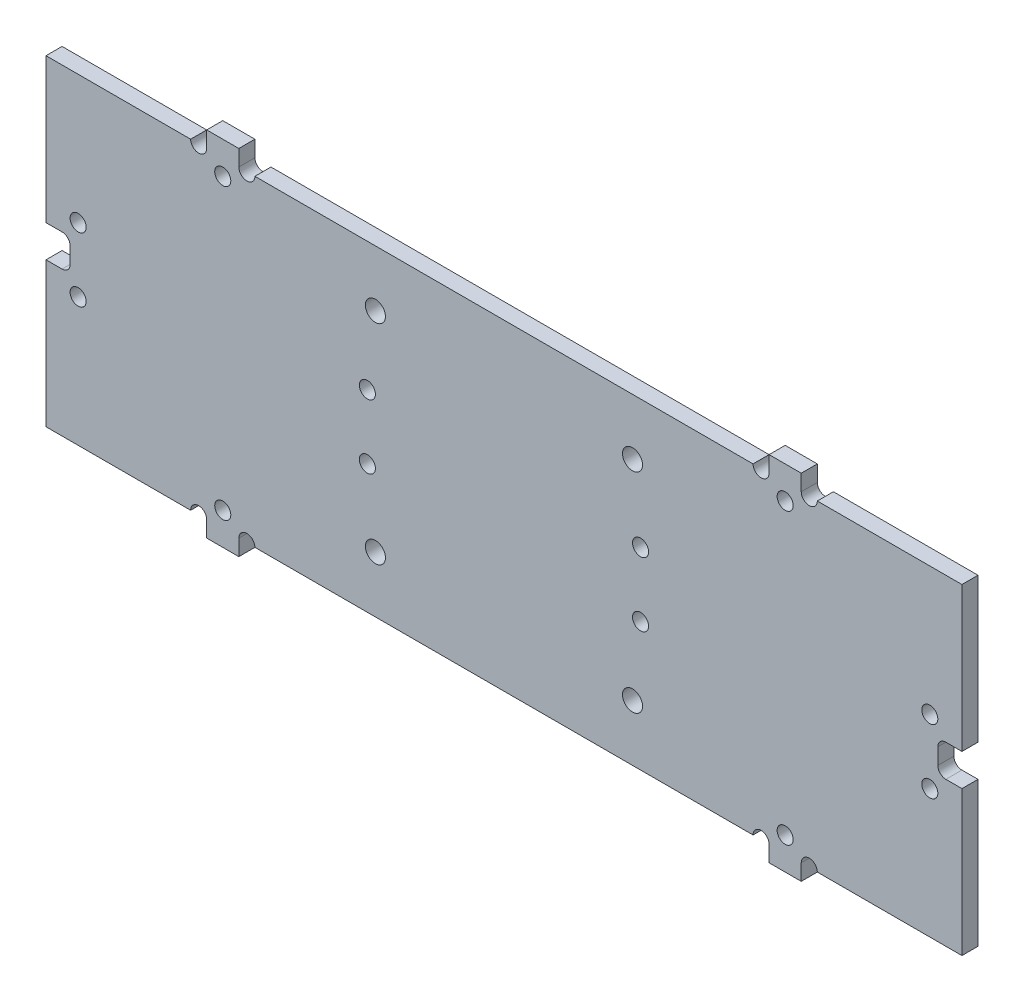
SolidWorks part; units mm, degrees
material "自訂玻璃纖維"
ref_plane "前基準面" through (0, 0, 0) normal (0, 0, 1) x (1, 0, 0)
ref_plane "上基準面" through (0, 0, 0) normal (0, 1, 0) x (1, 0, 0)
ref_plane "右基準面" through (0, 0, 0) normal (1, 0, 0) x (0, 0, -1)
sketch "草圖3" plane through (0, 0, 0) normal (0, 0, 1) x (1, 0, 0)
  line L0 (1, 40) -> (0, 40)
  line L1 (1, 0) -> (113, 0)
  line L2 (0, 1) -> (0, 39)
  line L3 (1, 40) -> (113, 40)
  line L4 (114, 1) -> (114, 39)
  line L5 (0, 40) -> (0, 39)
  line L6 (0, 1) -> (0, 0)
  line L7 (0, 0) -> (1, 0)
  line L8 (114, 1) -> (114, 0)
  line L9 (114, 0) -> (113, 0)
  line L10 (113, 40) -> (114, 40)
  line L11 (114, 40) -> (114, 39)
  circle A0 centre (4, 24) radius 1
  circle A1 centre (4, 16) radius 1
  circle A2 centre (110, 16) radius 1
  circle A3 centre (110, 24) radius 1
  point P9 (0, 20)
  point P16 (114, 0)
  point P19 (114, 40)
  point P22 (0, 0)
  point P25 (0, 40)
  point P26 (114, 20)
  dimension "D3" = 2
  dimension "D4" = 2
  dimension "D5" = 8
  dimension "D6" = 4
  dimension "D7" = 4
  dimension "D9" = 4
  dimension "D10" = 4
  dimension "D11" = 8
  dimension "D12" = 4
  dimension "D1" = 114
  dimension "D2" = 40
extrude "填料-伸長3" add sketch "草圖3" along normal blind 2
sketch "草圖4" plane through (0, 0, 2) normal (0, 0, 1) x (1, 0, 0)
  line L0 (0, 40) -> (0, 0) construction
  line L1 (114, 0) -> (114, 40) construction
  circle A0 centre (40, 24) radius 1
  circle A1 centre (40, 16) radius 1
  circle A2 centre (4, 24) radius 1 construction
  circle A3 centre (4, 16) radius 1 construction
  circle A4 centre (74, 16) radius 1
  circle A5 centre (74, 24) radius 1
  circle A6 centre (110, 24) radius 1 construction
  circle A7 centre (110, 16) radius 1 construction
  point P18 (0, 20)
  point P21 (114, 20)
  dimension "D1" = 2
  dimension "D2" = 2
  dimension "D3" = 36
  dimension "D4" = 36
  dimension "D5" = 36
  dimension "D6" = 36
  dimension "D7" = 8
  dimension "D8" = 4
  dimension "D9" = 4
  dimension "D10" = 4
extrude "除料-伸長2" cut sketch "草圖4" against normal blind 2
sketch "草圖6" plane through (0, 0, 2) normal (0, 0, 1) x (1, 0, 0)
  line L0 (0, 40) -> (0, 0) construction
  line L1 (114, 40) -> (0, 40) construction
  line L2 (0, 0) -> (114, 0) construction
  line L3 (114, 0) -> (114, 40) construction
  circle A2 centre (41, 33) radius 1.25
  circle A3 centre (73, 33) radius 1.25
  circle A4 centre (73, 7) radius 1.25
  circle A5 centre (41, 7) radius 1.25
  point P8 (0, 20)
  point P9 (57, 40)
  point P16 (57, 0)
  point P19 (114, 20)
  dimension "D1" = 2.5
  dimension "D2" = 32
  dimension "D3" = 26
  dimension "D4" = 16
  dimension "D5" = 32
  dimension "D6" = 26
  dimension "D7" = 13
  dimension "D8" = 16
  dimension "D9" = 13
extrude "除料-伸長6" cut sketch "草圖6" against normal blind 2
sketch "草圖7" plane through (0, 0, 2) normal (0, 0, 1) x (1, 0, 0)
  line L3 (114, 40) -> (0, 40) construction
  circle A1 centre (22, 38) radius 1
  circle A5 centre (92, 38) radius 1
  circle A6 centre (92, 2) radius 1
  circle A8 centre (22, 2) radius 1
  dimension "D2" = 2
  dimension "D6" = 2
  dimension "D8" = 2
extrude "除料-伸長7" cut sketch "草圖7" against normal blind 10
sketch "草圖8" plane through (0, 0, 2) normal (0, 0, 1) x (1, 0, 0)
  line L0 (114, 40) -> (0, 40) construction
  line L1 (20, 40) -> (24, 40)
  line L2 (20, 40) -> (20, 42)
  line L3 (20, 42) -> (24, 42)
  line L4 (24, 40) -> (24, 42)
  line L5 (20, 0) -> (24, 0)
  line L6 (20, -2) -> (20, 0)
  line L7 (24, -2) -> (24, 0)
  line L8 (20, -2) -> (24, -2)
  line L9 (90, 0) -> (94, 0)
  line L10 (90, -2) -> (90, 0)
  line L11 (94, -2) -> (94, 0)
  line L12 (90, -2) -> (94, -2)
  line L13 (90, 42) -> (94, 42)
  line L14 (90, 40) -> (90, 42)
  line L15 (94, 40) -> (94, 42)
  line L16 (90, 40) -> (94, 40)
  circle A0 centre (22, 38) radius 1 construction
  circle A1 centre (92, 38) radius 1 construction
  circle A2 centre (92, 2) radius 1 construction
  point P22 (94, -1)
  dimension "D1" = 4
  dimension "D2" = 2
  dimension "D3" = 2
  dimension "D4" = 2
  dimension "D5" = 2
extrude "填料-伸長6" add sketch "草圖8" against normal blind 2
sketch "草圖9" plane through (0, 0, 2) normal (0, 0, 1) x (1, 0, 0)
  line L0 (20, 40) -> (0, 40) construction
  line L1 (90, 40) -> (24, 40) construction
  line L2 (0, 0) -> (20, 0) construction
  line L3 (20, 0) -> (20, -2) construction
  line L4 (24, 0) -> (90, 0) construction
  line L5 (24, -2) -> (24, 0) construction
  line L6 (0, 40) -> (0, 0) construction
  line L7 (0, 22) -> (2, 22)
  line L8 (0, 22) -> (0, 18)
  line L9 (0, 18) -> (2, 18)
  line L10 (18, 40) -> (20, 40)
  line L11 (3, 21) -> (3, 19)
  line L12 (24, 40) -> (26, 40)
  line L13 (18, 0) -> (20, 0)
  line L14 (24, 0) -> (26, 0)
  line L16 (90, 0) -> (88, 0)
  line L17 (96, 0) -> (94, 0)
  line L18 (90, 40) -> (88, 40)
  line L19 (111, 21) -> (111, 19)
  line L20 (96, 40) -> (94, 40)
  line L21 (114, 18) -> (112, 18)
  line L22 (114, 22) -> (114, 18)
  line L23 (114, 22) -> (112, 22)
  arc A0 (20, 40) -> (18, 40) centre (19, 40) cw
  arc A1 (24, 40) -> (26, 40) centre (25, 40) ccw
  arc A2 (20, 0) -> (18, 0) centre (19, 0) ccw
  arc A3 (24, 0) -> (26, 0) centre (25, 0) cw
  circle A4 centre (4, 24) radius 1 construction
  arc A5 (2, 22) -> (3, 21) centre (2, 21) cw
  arc A6 (3, 19) -> (2, 18) centre (2, 19) cw
  arc A7 (111, 19) -> (112, 18) centre (112, 19) ccw
  arc A8 (112, 22) -> (111, 21) centre (112, 21) ccw
  arc A9 (90, 0) -> (88, 0) centre (89, 0) ccw
  arc A10 (94, 0) -> (96, 0) centre (95, 0) cw
  arc A11 (90, 40) -> (88, 40) centre (89, 40) cw
  arc A12 (94, 40) -> (96, 40) centre (95, 40) ccw
  dimension "D1" = 2
  dimension "D2" = 4
  dimension "D3" = 2
extrude "除料-伸長8" cut sketch "草圖9" against normal blind 2
